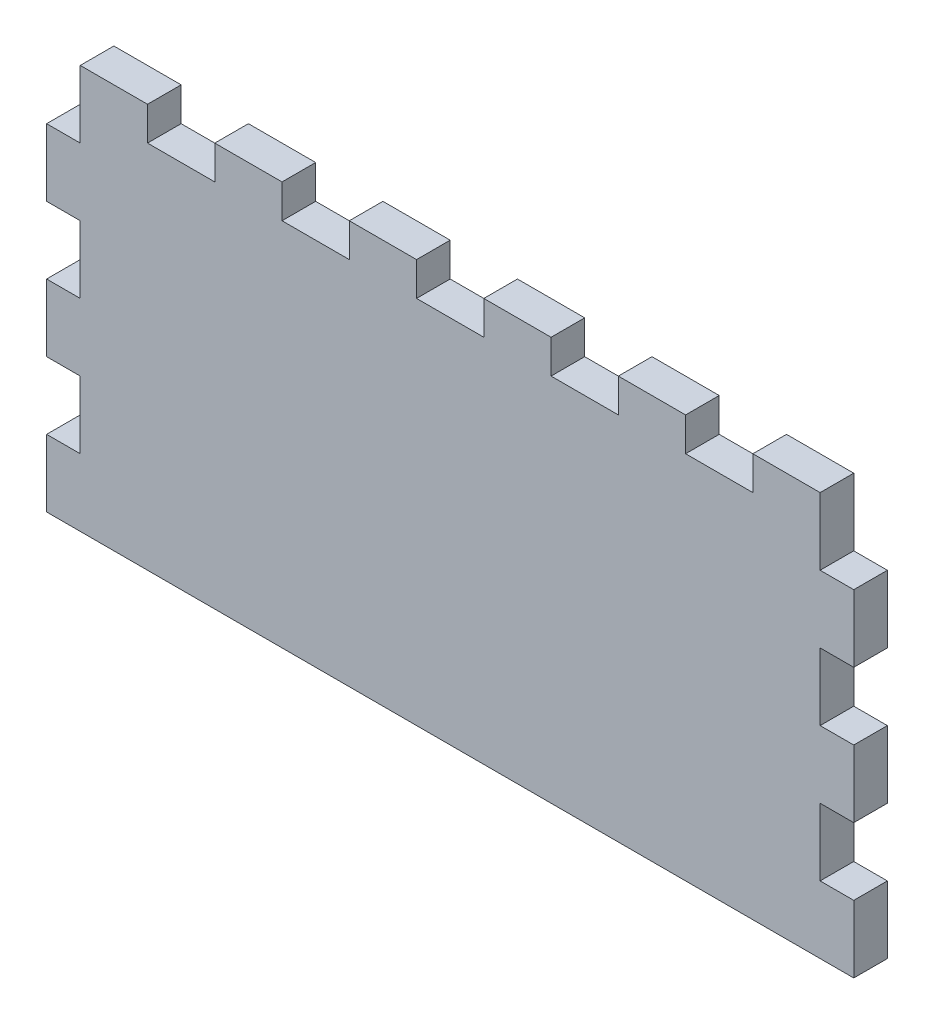
SolidWorks part; units mm, degrees
ref_plane "정면" through (0, 0, 0) normal (0, 0, 1) x (1, 0, 0)
ref_plane "윗면" through (0, 0, 0) normal (0, 1, 0) x (1, 0, 0)
ref_plane "우측면" through (0, 0, 0) normal (1, 0, 0) x (0, 0, -1)
sketch "스케치1" plane through (0, 0, 0) normal (0, 0, 1) x (1, 0, 0)
  line L1 (-60, 30) -> (60, 30)
  line L2 (-60, 30) -> (-60, -30)
  line L3 (-60, -30) -> (60, -30)
  line L4 (60, 30) -> (60, -30)
  line L5 (-60, 30) -> (60, -30) construction
  line L6 (-60, -30) -> (60, 30) construction
  point P0 (0, 0)
  dimension "D1" = 60
  dimension "D2" = 120
extrude "보스-돌출1" add sketch "스케치1" along normal blind 5
sketch "스케치2" plane through (0, 0, 5) normal (0, 0, 1) x (1, 0, 0)
  line L1 (-60, 30) -> (-55, 30)
  line L2 (-60, 30) -> (-60, 20)
  line L3 (-60, 20) -> (-55, 20)
  line L4 (-55, 30) -> (-55, 20)
  dimension "D1" = 5
  dimension "D2" = 10
extrude "컷-돌출1" cut sketch "스케치2" against normal up to next
pattern_linear "선형 패턴1" count 3 spacing 20 along (0, -1, 0) of "컷-돌출1"
mirror "대칭 복사1" about plane through (0, 0, 0) normal (1, 0, 0) of "선형 패턴1", "컷-돌출1"
sketch "스케치3" plane through (0, 0, 5) normal (0, 0, 1) x (1, 0, 0)
  line L0 (55, 30) -> (-55, 30) construction
  line L1 (-5, 30) -> (5, 30)
  line L2 (-5, 30) -> (-5, 25)
  line L3 (-5, 25) -> (5, 25)
  line L4 (5, 30) -> (5, 25)
  point P6 (0, 30)
  point P7 (0, 25)
  dimension "D1" = 10
  dimension "D2" = 5
extrude "컷-돌출2" cut sketch "스케치3" against normal up to next
pattern_linear "선형 패턴2" count 3 spacing 20 along (-1, 0, 0) of "컷-돌출2"
pattern_linear "선형 패턴3" count 3 spacing 20 along (1, 0, 0) of "컷-돌출2"
